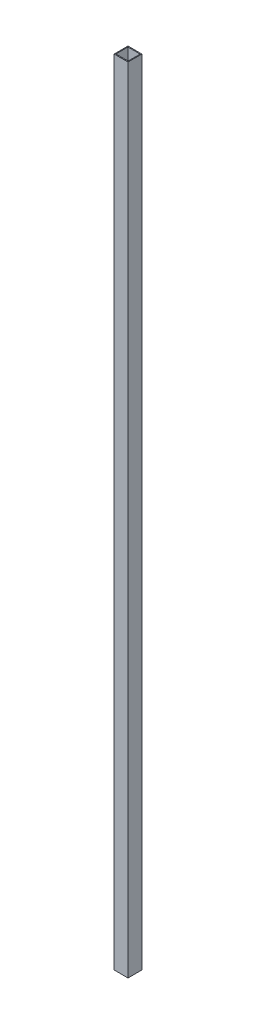
SolidWorks part; units mm, degrees
ref_plane "Front Plane" through (0, 0, 0) normal (0, 0, 1) x (1, 0, 0)
ref_plane "Top Plane" through (0, 0, 0) normal (0, 1, 0) x (1, 0, 0)
ref_plane "Right Plane" through (0, 0, 0) normal (1, 0, 0) x (0, 0, -1)
sketch "Sketch1" plane through (0, 0, 0) normal (0, 1, 0) x (1, 0, 0)
  line L1 (-10, 10) -> (10, 10)
  line L2 (-10, 10) -> (-10, -10)
  line L3 (-10, -10) -> (10, -10)
  line L4 (10, 10) -> (10, -10)
  line L5 (-10, 10) -> (10, -10) construction
  line L6 (-10, -10) -> (10, 10) construction
  point P0 (0, 0)
extrude "Boss-Extrude1" add sketch "Sketch1" along normal blind 1143
sketch "Sketch2" plane through (0, 0, 0) normal (0, -1, 0) x (1, 0, 0)
  line L1 (-8.8378, 8.6745) -> (8.8378, 8.6745)
  line L2 (-8.8378, 8.6745) -> (-8.8378, -8.6745)
  line L3 (-8.8378, -8.6745) -> (8.8378, -8.6745)
  line L4 (8.8378, 8.6745) -> (8.8378, -8.6745)
  line L5 (-8.8378, 8.6745) -> (8.8378, -8.6745) construction
  line L6 (-8.8378, -8.6745) -> (8.8378, 8.6745) construction
  point P0 (0, 0)
extrude "Cut-Extrude1" cut sketch "Sketch2" against normal blind 1143
